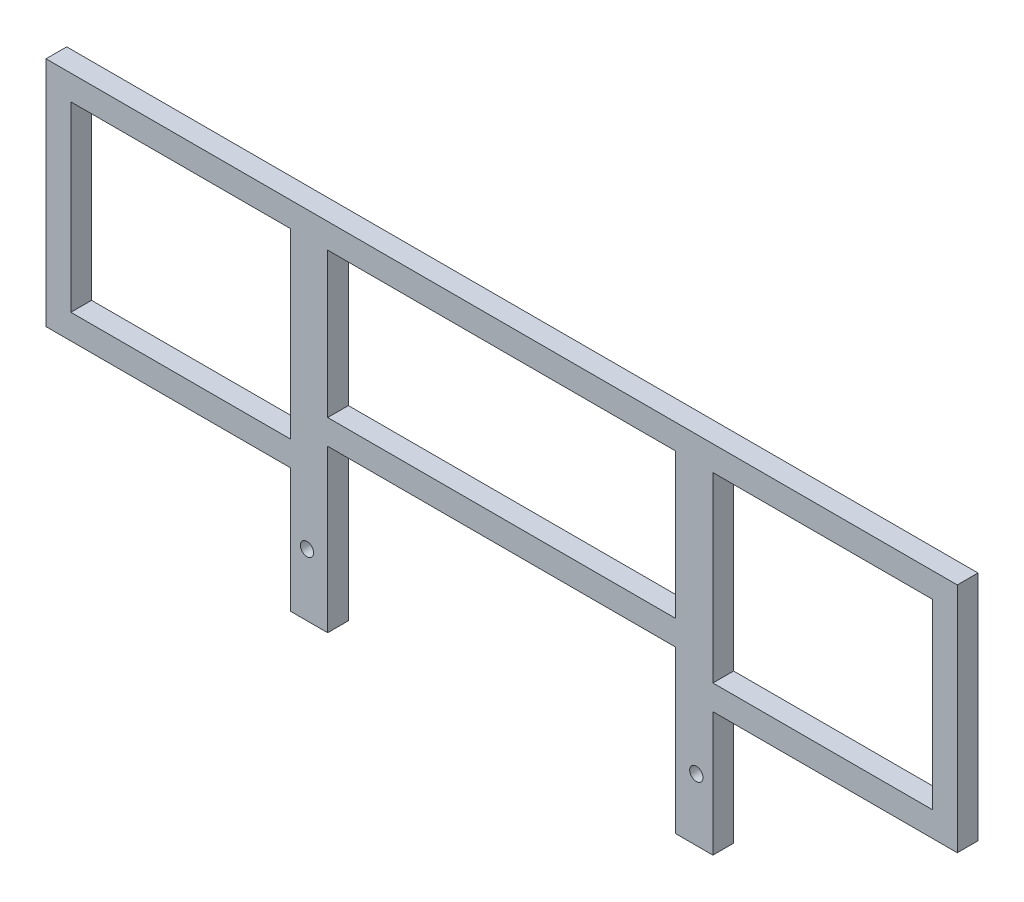
SolidWorks part; units mm, degrees
ref_plane "Front" through (0, 0, 0) normal (0, 0, 1) x (1, 0, 0)
ref_plane "Top" through (0, 0, 0) normal (0, 1, 0) x (1, 0, 0)
ref_plane "Right" through (0, 0, 0) normal (1, 0, 0) x (0, 0, -1)
sketch "草图1" plane through (0, 0, 0) normal (0, 0, 1) x (1, 0, 0)
  line L0 (161, 0) -> (220, 0)
  line L1 (0, 0) -> (59, 0)
  line L2 (0, 0) -> (0, 56)
  line L3 (0, 56) -> (220, 56)
  line L4 (220, 0) -> (220, 56)
  line L6 (59, 0) -> (59, -30)
  line L7 (59, -30) -> (68, -30)
  line L8 (161, 0) -> (161, -30)
  line L9 (152, -30) -> (161, -30)
  line L10 (6, 50) -> (59, 50)
  line L11 (6, 50) -> (6, 6)
  line L12 (6, 6) -> (59, 6)
  line L13 (59, 50) -> (59, 6)
  line L14 (161, 50) -> (214, 50)
  line L15 (161, 50) -> (161, 6)
  line L16 (161, 6) -> (214, 6)
  line L17 (214, 50) -> (214, 6)
  line L18 (68, 50) -> (152, 50)
  line L19 (68, 50) -> (68, 15)
  line L20 (68, 15) -> (152, 15)
  line L21 (152, 50) -> (152, 15)
  line L23 (68, -30) -> (68, 9)
  line L24 (68, 9) -> (152, 9)
  line L25 (152, -30) -> (152, 9)
  dimension "D1" = 220
  dimension "D2" = 56
  dimension "D3" = 30
  dimension "D4" = 102
  dimension "D6" = 6
  dimension "D7" = 6
  dimension "D8" = 6
  dimension "D9" = 0
  dimension "D10" = 6
  dimension "D11" = 6
  dimension "D12" = 6
  dimension "D13" = 0
  dimension "D14" = 9
  dimension "D15" = 9
  dimension "D16" = 35
  dimension "D17" = 6
  dimension "D18" = 6
extrude "凸台-拉伸1" add sketch "草图1" along normal blind 5
sketch "草图2" plane through (0, 0, 5) normal (0, 0, 1) x (1, 0, 0)
  line L0 (59, -30) -> (68, -30) construction
  line L1 (59, 0) -> (59, -30) construction
  line L2 (152, -30) -> (161, -30) construction
  line L3 (161, -30) -> (161, 0) construction
  circle A0 centre (63, -15) radius 1.6
  circle A1 centre (157, -15) radius 1.6
  dimension "D1" = 15
  dimension "D2" = 4
  dimension "D3" = 3.2
  dimension "D4" = 15
  dimension "D5" = 4
extrude "切除-拉伸1" cut sketch "草图2" against normal through all
